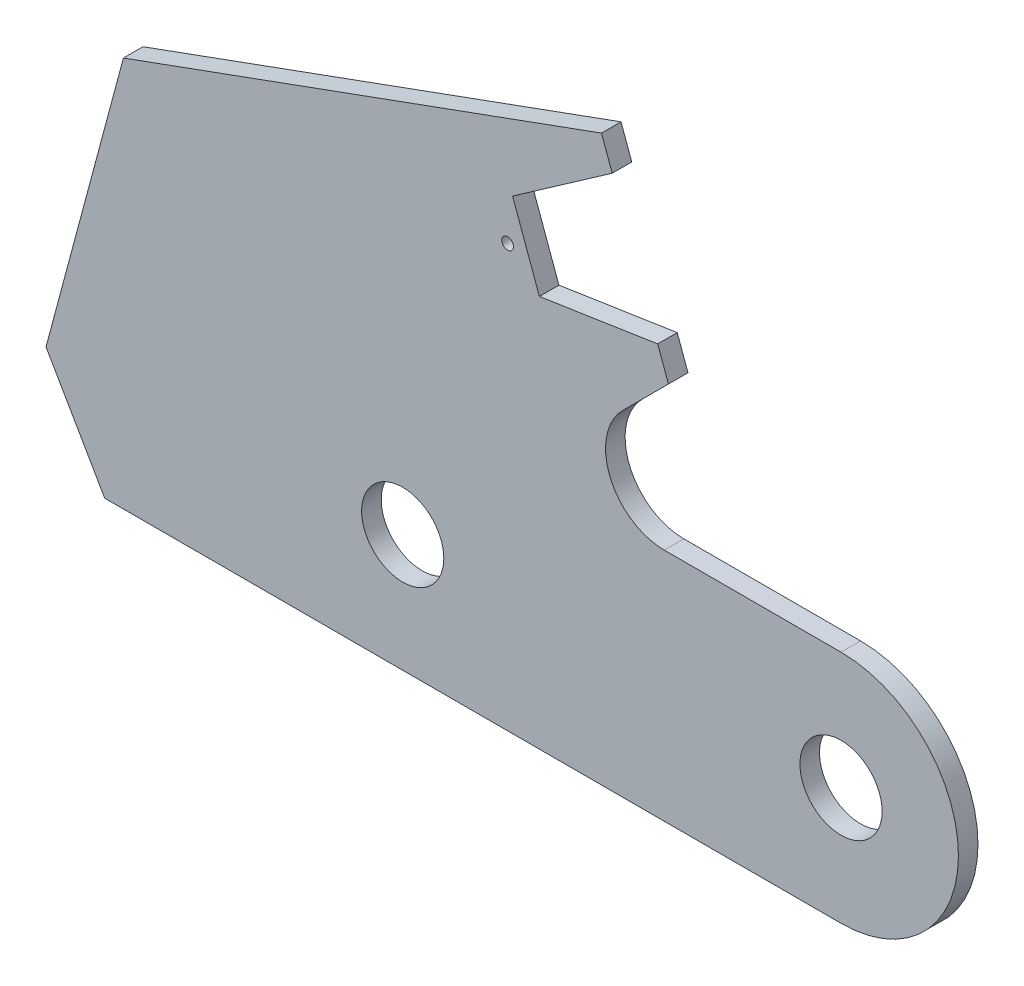
SolidWorks part; units mm, degrees
ref_plane "Front Plane" through (0, 0, 0) normal (0, 0, 1) x (1, 0, 0)
ref_plane "Top Plane" through (0, 0, 0) normal (0, 1, 0) x (1, 0, 0)
ref_plane "Right Plane" through (0, 0, 0) normal (1, 0, 0) x (0, 0, -1)
sketch "Sketch1" plane through (0, 0, 0) normal (0, 0, 1) x (1, 0, 0)
  line L0 (-17.6987, 77.2301) -> (94.3013, 77.2301) construction
  line L1 (94.3013, 107.2301) -> (12.9175, 107.2301)
  line L2 (94.3013, 107.2301) -> (94.3013, 47.2301) construction
  line L3 (94.3013, 47.2301) -> (-93.8447, 47.2301)
  line L5 (-93.8447, 47.2301) -> (-108.8447, 73.2109)
  line L6 (-108.8447, 73.2109) -> (-89.0647, 147.031)
  line L7 (-89.0647, 147.031) -> (33.0954, 191.4937)
  line L8 (33.0954, 191.4937) -> (50.1964, 144.509)
  line L9 (50.1964, 144.509) -> (12.9175, 107.2301)
  circle A0 centre (-17.6987, 77.2301) radius 10.5
  circle A1 centre (94.3013, 77.2301) radius 10.5
  arc A2 (94.3013, 47.2301) -> (94.3013, 107.2301) centre (94.3013, 77.2301) ccw
  dimension "D2" = 21
  dimension "D3" = 60
  dimension "D11" = 50
  dimension "D1" = 112
  dimension "D4" = 120
  dimension "D5" = 75
  dimension "D6" = 30
  dimension "D7" = 87
  dimension "D8" = 90
  dimension "D9" = 125
  dimension "D10" = 45
  dimension "D12" = 130
extrude "Boss-Extrude1" add sketch "Sketch1" along normal blind 5
fillet "Fillet1" radius 15 1 edges at (12.9175, 107.2301, 2.5)
sketch "Sketch2" plane through (0, 0, 5) normal (0, 0, 1) x (1, 0, 0)
  line L0 (35.8315, 183.9761) -> (10.3769, 166.198)
  line L1 (50.1964, 144.509) -> (33.0954, 191.4937) construction
  line L2 (10.3769, 166.198) -> (17.2173, 147.4041)
  line L3 (17.2173, 147.4041) -> (47.4602, 152.0266)
  line L4 (35.8315, 183.9761) -> (47.4602, 152.0266)
  line L5 (33.0954, 191.4937) -> (-89.0647, 147.031) construction
  line L6 (9.0987, 155.0909) -> (13.7971, 156.801) construction
  circle A0 centre (9.0987, 155.0909) radius 1.5
  dimension "D7" = 3
  dimension "D1" = 8
  dimension "D2" = 8
  dimension "D3" = 20
  dimension "D4" = 30
  dimension "D5" = 16
  dimension "D6" = 5
extrude "Cut-Extrude1" cut sketch "Sketch2" against normal blind 5
